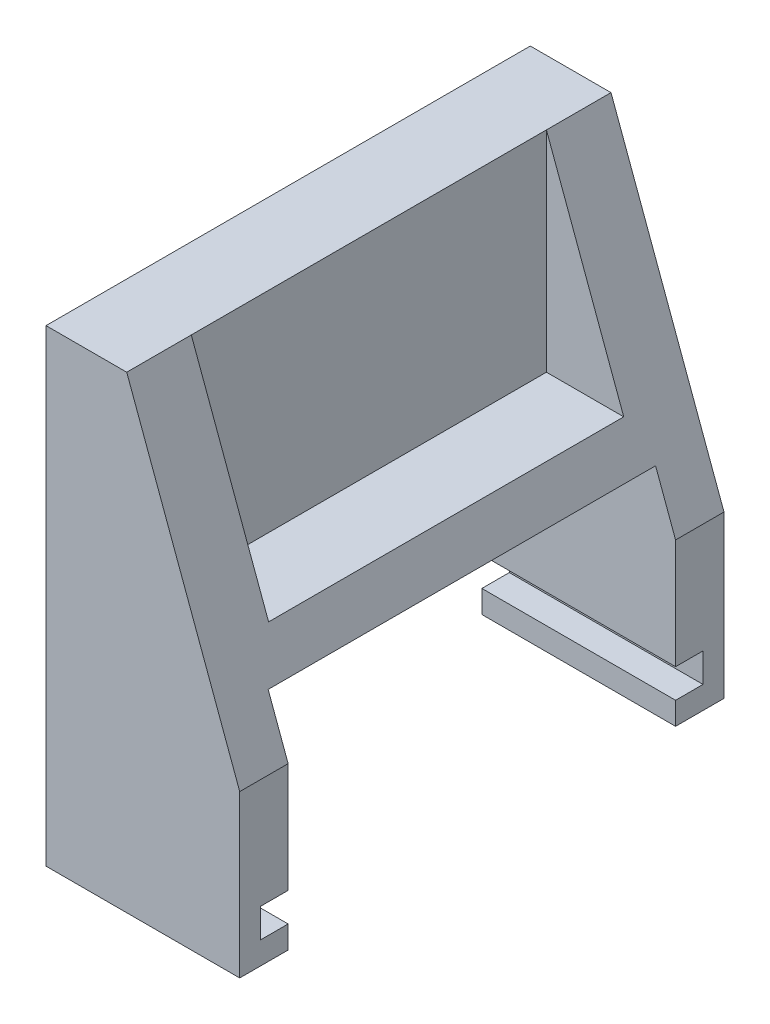
SolidWorks part; units mm, degrees
ref_plane "Front Plane" through (0, 0, 0) normal (0, 0, 1) x (1, 0, 0)
ref_plane "Top Plane" through (0, 0, 0) normal (0, 1, 0) x (1, 0, 0)
ref_plane "Right Plane" through (0, 0, 0) normal (1, 0, 0) x (0, 0, -1)
sketch "Sketch1" plane through (0, 0, 0) normal (0, 0, 1) x (1, 0, 0)
  line L0 (0, 0) -> (0, -29)
  line L1 (0, -29) -> (12, -29)
  line L2 (12, -29) -> (12, -19)
  line L3 (12, -19) -> (5, 0)
  line L4 (5, 0) -> (0, 0)
  dimension "D1" = 29
  dimension "D2" = 12
  dimension "D3" = 10
  dimension "D4" = 5
extrude "Boss-Extrude1" add sketch "Sketch1" against normal blind 30
sketch "Sketch4" plane through (0, 0, 0) normal (-1, 0, 0) x (0, 0, 1)
  line L0 (-30, 0) -> (-30, -29) construction
  line L1 (-27, -15.6386) -> (-3, -15.6386)
  line L2 (-27, -15.6386) -> (-27, -29.6386)
  line L3 (-27, -29.6386) -> (-3, -29.6386)
  line L4 (-3, -15.6386) -> (-3, -29.6386)
  point P4 (-27, -22.6386)
  dimension "D1" = 24
  dimension "D2" = 14
  dimension "D3" = 3
extrude "Cut-Extrude2" cut sketch "Sketch4" against normal blind 25 contours L2 L1 L4 L3
sketch "Sketch5" plane through (0, 0, 0) normal (-1, 0, 0) x (0, 0, 1)
  line L0 (-3, -15.6386) -> (-3, -29) construction
  line L1 (-3, -25.8) -> (-1.3, -25.8)
  line L2 (-3, -25.8) -> (-3, -27.6)
  line L3 (-3, -27.6) -> (-1.3, -27.6)
  line L4 (-1.3, -25.8) -> (-1.3, -27.6)
  line L5 (-3, -29) -> (0, -29) construction
  dimension "D1" = 1.8
  dimension "D2" = 1.7
  dimension "D3" = 1.4
extrude "Cut-Extrude3" cut sketch "Sketch5" against normal blind 15
ref_plane "Plane1" through (0, 0, -15) normal (0, 0, 1) x (1, 0, 0)
mirror "Mirror1" about plane through (0, 0, -15) normal (0, 0, 1) of "Cut-Extrude3"
sketch "Sketch6" plane through (0, 0, -15) normal (0, 0, 1) x (1, 0, 0)
  line L0 (5, 0) -> (5, -13)
  line L1 (5, -13) -> (9.7895, -13)
  line L2 (12, -19) -> (5, 0) construction
  line L3 (9.7895, -13) -> (5, 0)
  dimension "D1" = 13
extrude "Cut-Extrude4" cut sketch "Sketch6" against normal mid plane 22
ref_plane "Plane2" through (0, -15, 0) normal (0, 1, 0) x (1, 0, 0)
